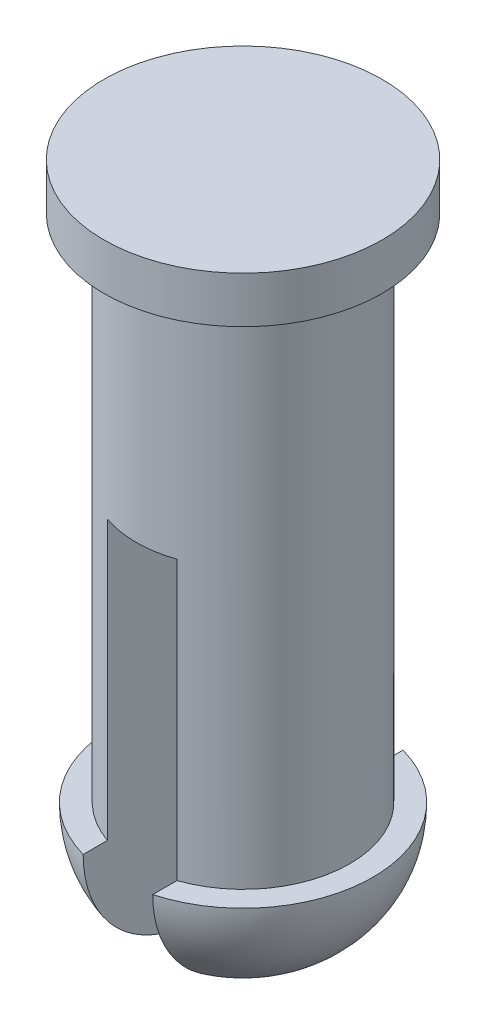
SolidWorks part; units mm, degrees
material "PVC Rigid"
ref_plane "Front Plane" through (0, 0, 0) normal (0, 0, 1) x (1, 0, 0)
ref_plane "Top Plane" through (0, 0, 0) normal (0, 1, 0) x (1, 0, 0)
ref_plane "Right Plane" through (0, 0, 0) normal (1, 0, 0) x (0, 0, -1)
sketch "Sketch1" plane through (0, 0, 0) normal (0, 0, 1) x (1, 0, 0)
  line L0 (0, 0) -> (0, 3.048)
  line L1 (0, 3.048) -> (0.762, 3.048)
  line L2 (0.762, 3.048) -> (0.762, 2.794)
  line L3 (0.762, 2.794) -> (0.5842, 2.794)
  line L4 (0.5842, 2.794) -> (0.5842, 0)
  line L5 (0.5842, 0) -> (0.7112, 0)
  line L6 (0, -0.635) -> (0, 0)
  line L7 (0, -1000) -> (0, 49000) construction
  arc A0 (0.7112, 0) -> (0, -0.635) centre (0.0721, 0) cw
  dimension "D1" = 3.048
  dimension "D2" = 2.794
  dimension "D3" = 0.762
  dimension "D4" = 0.5842
  dimension "D5" = 0.254
  dimension "D6" = 0.127
  dimension "D7" = 0.635
revolve "Revolve1" add sketch "Sketch1" angle 360 about L7
sketch "Sketch4" plane through (0, 0, 0) normal (0, 0, 1) x (1, 0, 0)
  line L0 (-0.1905, 0) -> (-0.1905, 1.524)
  line L1 (0.7112, 0) -> (-0.7112, 0) construction
  line L2 (-0.1905, 1.524) -> (0.1905, 1.524)
  line L3 (0.1905, 1.524) -> (0.1905, -0.6604)
  line L4 (0.1905, -0.6604) -> (-0.1905, -0.6604)
  line L5 (-0.1905, -0.6604) -> (-0.1905, 0)
  line L6 (0, 0) -> (0, -0.6604) construction
  dimension "D1" = 1.524
  dimension "D2" = 0.381
  dimension "D3" = 0.6604
extrude "Cut-Extrude11" cut sketch "Sketch4" against normal mid plane 2.54
